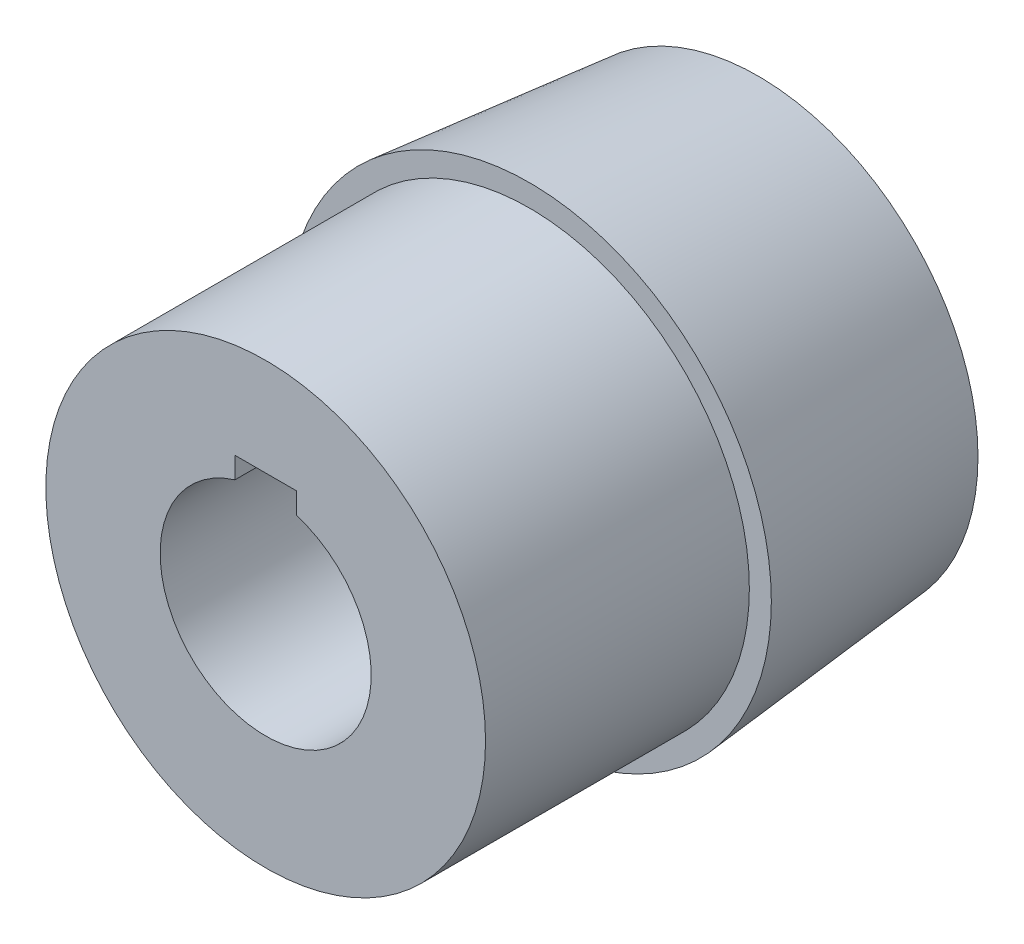
SolidWorks part; units mm, degrees
ref_plane "Front Plane" through (0, 0, 0) normal (0, 0, 1) x (1, 0, 0)
ref_plane "Top Plane" through (0, 0, 0) normal (0, 1, 0) x (1, 0, 0)
ref_plane "Right Plane" through (0, 0, 0) normal (1, 0, 0) x (0, 0, -1)
sketch "Sketch1" plane through (0, 0, 0) normal (0, 0, 1) x (1, 0, 0)
  circle A0 centre (0, 0) radius 55
  dimension "D1" = 110
extrude "Boss-Extrude1" add sketch "Sketch1" along normal mid plane 112
sketch "Sketch2" plane through (0, 0, 56) normal (0, 0, 1) x (1, 0, 0)
  circle A0 centre (0, 0) radius 24
  dimension "D1" = 48
extrude "Cut-Extrude1" cut sketch "Sketch2" against normal blind 112
sketch "Sketch3" plane through (0, 0, 56) normal (0, 0, 1) x (1, 0, 0)
  line L1 (-7, 20.2) -> (7, 20.2)
  line L2 (-7, 20.2) -> (-7, 27.8)
  line L3 (-7, 27.8) -> (7, 27.8)
  line L4 (7, 20.2) -> (7, 27.8)
  line L5 (-7, 20.2) -> (7, 27.8) construction
  line L6 (-7, 27.8) -> (7, 20.2) construction
  circle A0 centre (0, 0) radius 24 construction
  point P0 (0, 24)
  dimension "D1" = 14
  dimension "D2" = 3.8
extrude "Cut-Extrude2" cut sketch "Sketch3" against normal through all
sketch "Sketch4" plane through (0, 0, 56) normal (0, 0, 1) x (1, 0, 0)
  circle A0 centre (0, 0) radius 50
  dimension "D1" = 100
extrude "Cut-Extrude3" cut sketch "Sketch4" against normal blind 60 flip side to cut contours A0
sketch "Sketch5" plane through (0, 0, 0) normal (0, 1, 0) x (1, 0, 0)
  line L0 (50, 56) -> (55, 4)
  line L3 (55, 56) -> (-55, 56) construction
  line L4 (55, 4) -> (55, 56)
  line L5 (0, 0) -> (0, 120.9951) construction
  line L6 (55, 56) -> (50, 56)
  line L7 (50, -56) -> (50, 4) construction
revolve "Cut-Revolve1" cut sketch "Sketch5" angle 360 about L5
hole_wizard "M10x1.0 Tapped Hole1" positions "Sketch7" profile "Sketch6" tap size "M10x1.0" standard "ISO"
sketch "Sketch7" plane through (-4.8677, -29.2568, -56) normal (0, 0, 1) x (1, 0, 0)
  point P0 (41.8677, 29.2568)
  point P2 (-32.1323, 29.2568)
  dimension "D1" = 37
  dimension "D2" = 37
sketch "Sketch6" plane through (37, 0, -56) normal (1, 0, 0) x (0, 1, 0)
  line L0 (0, 0) -> (0, 30.7039)
  line L1 (0, 30.7039) -> (4.5, 28)
  line L2 (4.5, 28) -> (4.5, 0)
  line L5 (4.5, 0) -> (0, 0)
  line L10 (0, 30.7039) -> (-4.5, 28) construction
  line L11 (0, -6.35) -> (0, 107.95) construction
  dimension "Tap Drill Dia." = 9
  dimension "Tap Drill Depth" = 28
  dimension "Drill Angle" = 118
cosmetic thread "Hole Thread1" parameters "D1"=25, "D2"=12
cosmetic thread "Hole Thread2" parameters "D1"=25, "D2"=12
